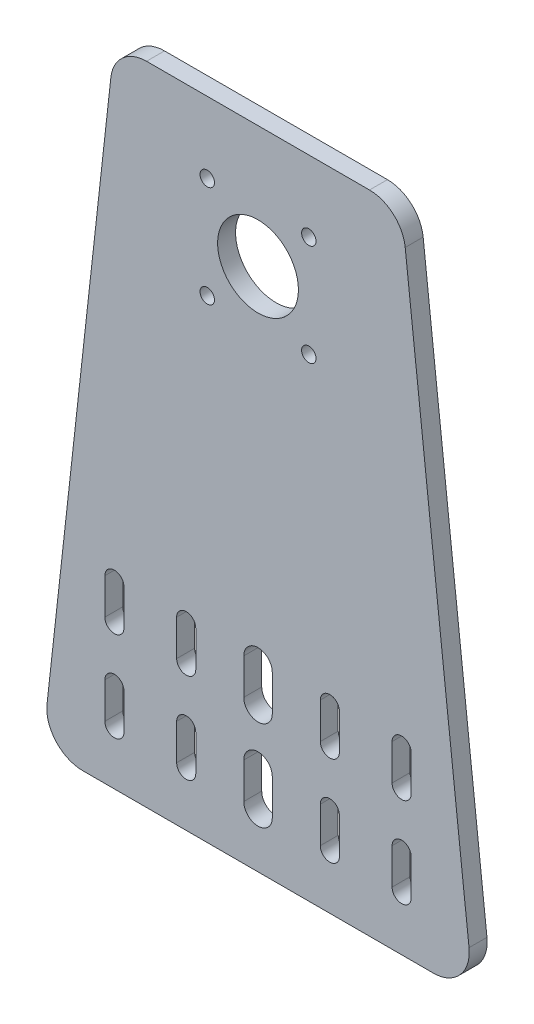
SolidWorks part; units mm, degrees
ref_plane "Front Plane" through (0, 0, 0) normal (0, 0, 1) x (1, 0, 0)
ref_plane "Top Plane" through (0, 0, 0) normal (0, 1, 0) x (1, 0, 0)
ref_plane "Right Plane" through (0, 0, 0) normal (1, 0, 0) x (0, 0, -1)
sketch "Sketch1" plane through (0, 0, 0) normal (0, 0, 1) x (1, 0, 0)
  line L0 (14.1893, 0) -> (138.2107, 0)
  line L5 (20.6079, 185.4708) -> (131.7921, 185.4708) construction
  line L6 (115.633, 228.6) -> (36.767, 228.6)
  line L7 (1.5669, 14.1025) -> (24.1447, 217.3025)
  line L12 (150.8331, 14.1025) -> (128.2553, 217.3025)
  line L14 (76.2, 0) -> (76.2, 228.6) construction
  line L15 (2.1167, 19.05) -> (150.2833, 19.05) construction
  line L16 (76.2, 185.4708) -> (94.1605, 203.4313) construction
  line L17 (101.6, 19.05) -> (101.6, 31.75) construction
  line L18 (98.2218, 19.05) -> (98.2218, 31.75)
  line L19 (104.9782, 19.05) -> (104.9782, 31.75)
  line L20 (76.2, 19.05) -> (76.2, 31.75) construction
  line L21 (71.1581, 19.05) -> (71.1581, 31.75)
  line L22 (81.2419, 19.05) -> (81.2419, 31.75)
  line L23 (130.3782, 19.05) -> (130.3782, 31.75)
  line L24 (123.6218, 19.05) -> (123.6218, 31.75)
  line L25 (127, 19.05) -> (127, 31.75) construction
  line L26 (50.8, 19.05) -> (50.8, 31.75) construction
  line L27 (54.1782, 19.05) -> (54.1782, 31.75)
  line L28 (47.4218, 19.05) -> (47.4218, 31.75)
  line L29 (25.4, 19.05) -> (25.4, 31.75) construction
  line L30 (28.7782, 19.05) -> (28.7782, 31.75)
  line L31 (22.0218, 19.05) -> (22.0218, 31.75)
  line L32 (6.7197, 60.4774) -> (145.6803, 60.4774) construction
  line L33 (28.7782, 50.9524) -> (28.7782, 63.6524)
  line L34 (22.0218, 50.9524) -> (22.0218, 63.6524)
  line L35 (54.1782, 50.9524) -> (54.1782, 63.6524)
  line L36 (47.4218, 50.9524) -> (47.4218, 63.6524)
  line L37 (81.2419, 50.9524) -> (81.2419, 63.6524)
  line L38 (71.1581, 50.9524) -> (71.1581, 63.6524)
  line L39 (104.9782, 50.9524) -> (104.9782, 63.6524)
  line L40 (98.2218, 50.9524) -> (98.2218, 63.6524)
  line L41 (123.6218, 50.9524) -> (123.6218, 63.6524)
  line L42 (130.3782, 50.9524) -> (130.3782, 63.6524)
  line L43 (101.6, 50.9524) -> (101.6, 63.6524) construction
  line L44 (76.2, 50.9524) -> (76.2, 63.6524) construction
  line L45 (127, 50.9524) -> (127, 63.6524) construction
  line L46 (50.8, 50.9524) -> (50.8, 63.6524) construction
  line L47 (25.4, 50.9524) -> (25.4, 63.6524) construction
  circle A12 centre (76.2, 185.4708) radius 14.2875
  arc A18 (24.1447, 217.3025) -> (36.767, 228.6) centre (36.767, 215.9) cw
  arc A19 (128.2553, 217.3025) -> (115.633, 228.6) centre (115.633, 215.9) ccw
  arc A20 (150.8331, 14.1025) -> (138.2107, 0) centre (138.2107, 12.7) cw
  arc A21 (14.1893, 0) -> (1.5669, 14.1025) centre (14.1893, 12.7) cw
  circle A22 centre (76.2, 185.4708) radius 25.4 construction
  circle A23 centre (94.1605, 203.4313) radius 2.5527
  circle A24 centre (94.1605, 167.5103) radius 2.5527
  circle A25 centre (58.2395, 167.5103) radius 2.5527
  circle A26 centre (58.2395, 203.4313) radius 2.5527
  arc A27 (98.2218, 19.05) -> (104.9782, 19.05) centre (101.6, 19.05) ccw
  arc A28 (104.9782, 31.75) -> (98.2218, 31.75) centre (101.6, 31.75) ccw
  arc A29 (71.1581, 19.05) -> (81.2419, 19.05) centre (76.2, 19.05) ccw
  arc A30 (81.2419, 31.75) -> (71.1581, 31.75) centre (76.2, 31.75) ccw
  arc A31 (123.6218, 19.05) -> (130.3782, 19.05) centre (127, 19.05) ccw
  arc A32 (130.3782, 31.75) -> (123.6218, 31.75) centre (127, 31.75) ccw
  arc A33 (54.1782, 19.05) -> (47.4218, 19.05) centre (50.8, 19.05) cw
  arc A34 (47.4218, 31.75) -> (54.1782, 31.75) centre (50.8, 31.75) cw
  arc A35 (28.7782, 19.05) -> (22.0218, 19.05) centre (25.4, 19.05) cw
  arc A36 (22.0218, 31.75) -> (28.7782, 31.75) centre (25.4, 31.75) cw
  arc A37 (22.0218, 63.6524) -> (28.7782, 63.6524) centre (25.4, 63.6524) cw
  arc A38 (28.7782, 50.9524) -> (22.0218, 50.9524) centre (25.4, 50.9524) cw
  arc A39 (47.4218, 63.6524) -> (54.1782, 63.6524) centre (50.8, 63.6524) cw
  arc A40 (54.1782, 50.9524) -> (47.4218, 50.9524) centre (50.8, 50.9524) cw
  arc A41 (71.1581, 50.9524) -> (81.2419, 50.9524) centre (76.2, 50.9524) ccw
  arc A42 (81.2419, 63.6524) -> (71.1581, 63.6524) centre (76.2, 63.6524) ccw
  arc A43 (98.2218, 50.9524) -> (104.9782, 50.9524) centre (101.6, 50.9524) ccw
  arc A44 (104.9782, 63.6524) -> (98.2218, 63.6524) centre (101.6, 63.6524) ccw
  arc A45 (130.3782, 63.6524) -> (123.6218, 63.6524) centre (127, 63.6524) ccw
  arc A46 (123.6218, 50.9524) -> (130.3782, 50.9524) centre (127, 50.9524) ccw
  point P16 (101.6, 25.4)
  point P21 (76.2, 25.4)
  point P24 (25.4, 228.6)
  point P27 (127, 228.6)
  point P30 (152.4, 0)
  point P33 (0, 0)
  point P47 (76.2, 185.4708)
  point P53 (127, 25.4)
  point P58 (50.8, 25.4)
  point P65 (25.4, 25.4)
  point P78 (101.6, 57.3024)
  point P83 (76.2, 57.3024)
  point P92 (127, 57.3024)
  point P97 (50.8, 57.3024)
  point P104 (25.4, 57.3024)
  dimension "D1" = 152.4
  dimension "D3" = 19.05
  dimension "D4" = 101.6
  dimension "D5" = 76.2
  dimension "D7" = 6.7564
  dimension "D8" = 166.4208
  dimension "D6" = 10.0838
  dimension "D9" = 12.7
  dimension "D10" = 45
  dimension "D11" = 5.1054
  dimension "D2" = 228.6
  dimension "D12" = 12.7
  dimension "D13" = 12.7
  dimension "D14" = 25.4
  dimension "D16" = 124.9934
  dimension "D15" = 2
  dimension "D17" = 2
extrude "Boss-Extrude1" add sketch "Sketch1" along normal blind 6.35
